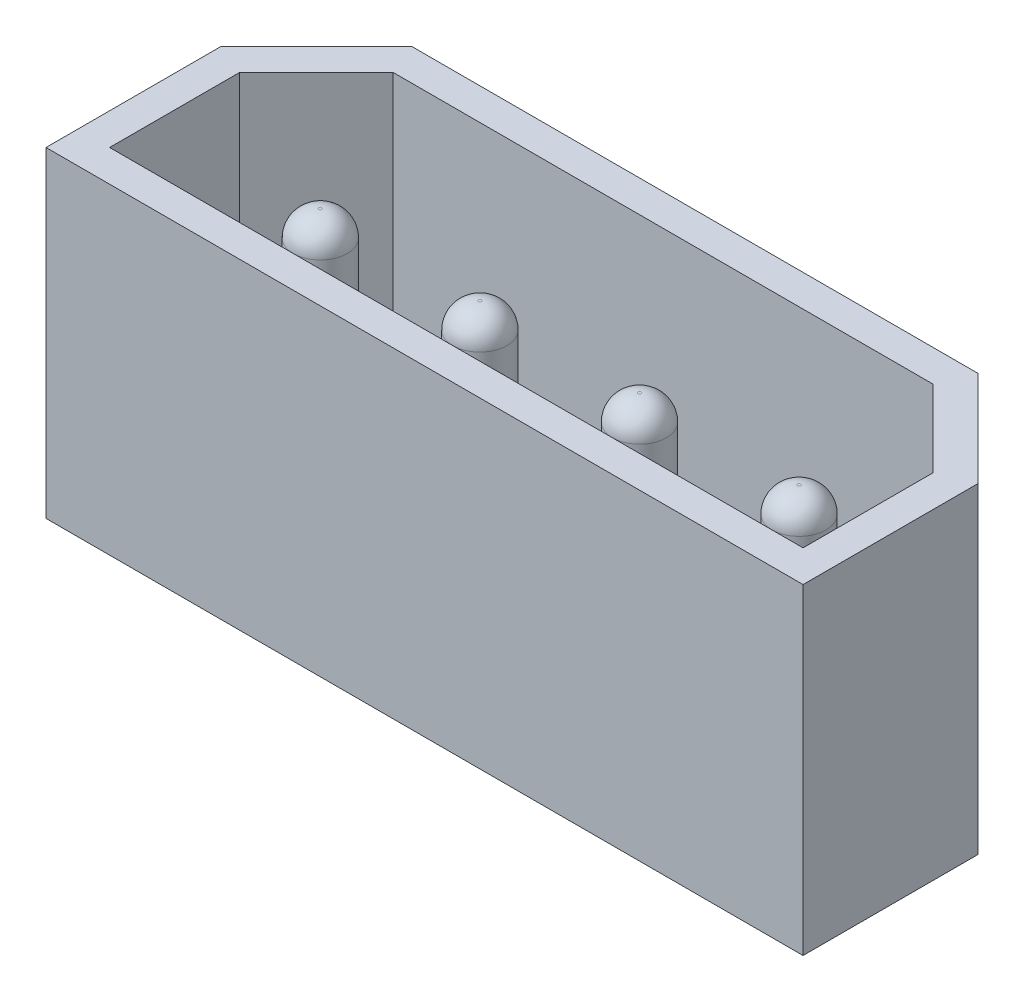
SolidWorks part; units mm, degrees
ref_plane "Front Plane" through (0, 0, 0) normal (0, 0, 1) x (1, 0, 0)
ref_plane "Top Plane" through (0, 0, 0) normal (0, 1, 0) x (1, 0, 0)
ref_plane "Right Plane" through (0, 0, 0) normal (1, 0, 0) x (0, 0, -1)
sketch "Sketch2" plane through (0, 0, 0) normal (0, 1, 0) x (1, 0, 0)
  line L0 (0, 30.3196) -> (0, -26.4148) construction
  line L1 (-29.4008, 0) -> (31.4681, 0) construction
  line L2 (-11.9, 1.25) -> (-8.9, 4.25)
  line L3 (-8.9, 4.25) -> (8.9, 4.25)
  line L4 (-11.9, 1.25) -> (-11.9, -4.25)
  line L5 (-11.9, -4.25) -> (11.9, -4.25)
  line L6 (11.9, 1.25) -> (11.9, -4.25)
  line L7 (-11.9, 4.25) -> (11.9, -4.25) construction
  line L8 (-11.9, -4.25) -> (11.9, 4.25) construction
  line L9 (8.9, 4.25) -> (11.9, 1.25)
  line L10 (-10.9, 0.8358) -> (-10.9, -3.25) construction
  line L11 (-10.9, -3.25) -> (10.9, -3.25) construction
  line L12 (10.9, 0.8358) -> (10.9, -3.25) construction
  line L13 (8.4858, 3.25) -> (10.9, 0.8358) construction
  line L14 (-8.4858, 3.25) -> (8.4858, 3.25) construction
  line L15 (-10.9, 0.8358) -> (-8.4858, 3.25) construction
  point P5 (0, 0)
  dimension "D1" = 23.8
  dimension "D2" = 8.5
  dimension "D3" = 1
extrude "Boss-Extrude1" add sketch "Sketch2" along normal blind 10.1
shell "Shell1" thickness 1
sketch "Sketch3" plane through (0, 1, 0) normal (0, 1, 0) x (1, 0, 0)
  line L0 (0, 6.137) -> (0, -5.9677) construction
  line L1 (-12.6125, 0) -> (14.6229, 0) construction
  line L2 (-8.375, 0) -> (-8.375, -2.1968) construction
  line L3 (8.375, 0) -> (8.375, -2.1968) construction
  circle A0 centre (-7.525, 0) radius 0.85
  circle A1 centre (-2.5088, 0) radius 0.85
  circle A2 centre (7.525, 0) radius 0.85
  circle A3 centre (2.5088, 0) radius 0.85
  point P17 (0, 0)
  dimension "D1" = 1.7
  dimension "D3" = 16.75
  dimension "D4" = 5.0175
  dimension "D2" = 2
extrude "Boss-Extrude2" add sketch "Sketch3" along normal blind 7.5 and the other way blind 4
fillet "Fillet2" radius 0.8 8 edges at (7.525, 8.5, -0.85) (2.5088, 8.5, -0.85) (-2.5088, 8.5, 0.85) (-7.525, 8.5, 0.85) (-7.525, -3, 0.85) (-2.5088, -3, 0.85) (2.5088, -3, -0.85) (7.525, -3, -0.85)
sketch "Sketch4" plane through (0, 0, 0) normal (0, -1, 0) x (1, 0, 0)
  line L0 (8.9, -4.25) -> (-8.9, -4.25) construction
  line L1 (-12.1681, -1.85) -> (14.4536, -1.85)
  line L2 (-12.1681, -1.85) -> (-12.1681, -3.45)
  line L3 (-12.1681, -3.45) -> (14.4536, -3.45)
  line L4 (14.4536, -1.85) -> (14.4536, -3.45)
  dimension "D1" = 1.6
  dimension "D2" = 0.8
extrude "Cut-Extrude1" cut sketch "Sketch4" against normal blind 0.8
